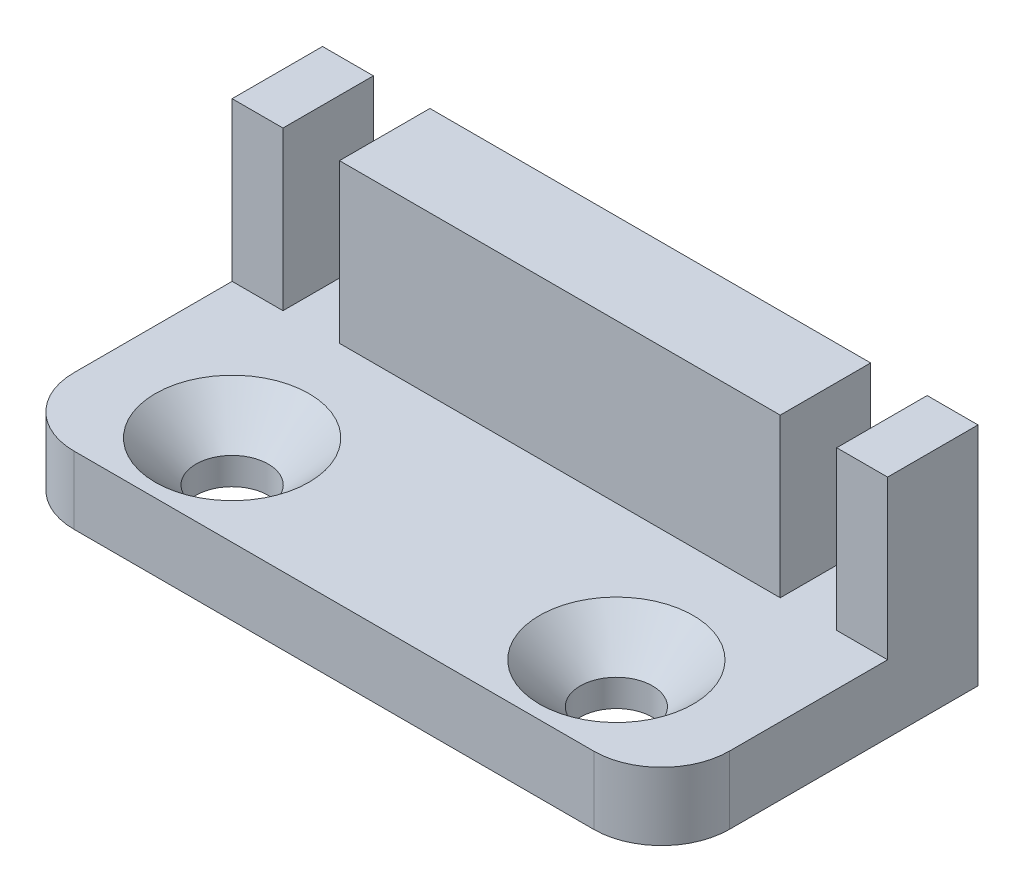
SolidWorks part; units mm, degrees
ref_plane "Front Plane" through (0, 0, 0) normal (0, 0, 1) x (1, 0, 0)
ref_plane "Top Plane" through (0, 0, 0) normal (0, 1, 0) x (1, 0, 0)
ref_plane "Right Plane" through (0, 0, 0) normal (1, 0, 0) x (0, 0, -1)
sketch "Sketch7" plane through (0, 0, 0) normal (0, 0, 1) x (1, 0, 0)
  line L1 (0, 0) -> (29, 0)
  line L2 (0, 0) -> (0, 10)
  line L3 (0, 10) -> (29, 10)
  line L4 (29, 0) -> (29, 10)
  dimension "D1" = 10
  dimension "D2" = 29
extrude "Boss-Extrude5" add sketch "Sketch7" along normal blind 4
sketch "Sketch8" plane through (0, 0, 4) normal (0, 0, 1) x (1, 0, 0)
  line L0 (29, 0) -> (29, 10) construction
  line L1 (0, 0) -> (29, 0)
  line L2 (0, 0) -> (0, 3)
  line L3 (0, 3) -> (29, 3)
  line L4 (29, 0) -> (29, 3)
  dimension "D1" = 3
extrude "Boss-Extrude6" add sketch "Sketch8" along normal blind 10
sketch "Sketch9" plane through (0, 10, 0) normal (0, 1, 0) x (1, 0, 0)
  line L0 (29, 0) -> (0, 0) construction
  line L1 (4.75, 0) -> (2.25, 0)
  line L2 (4.75, 0) -> (4.75, -4)
  line L3 (4.75, -4) -> (2.25, -4)
  line L4 (2.25, 0) -> (2.25, -4)
  line L5 (29, -4) -> (0, -4) construction
  line L6 (3.5, 0) -> (3.5, -4) construction
  line L11 (0, -4) -> (0, 0) construction
  line L12 (14.5, 0) -> (14.5, -14) construction
  line L13 (29, -14) -> (0, -14) construction
  line L16 (24.25, -4) -> (26.75, -4)
  line L17 (26.75, 0) -> (26.75, -4)
  line L18 (24.25, 0) -> (26.75, 0)
  line L23 (24.25, 0) -> (24.25, -4)
  dimension "D1" = 3.5
  dimension "D2" = 2.5
extrude "Cut-Extrude2" cut sketch "Sketch9" against normal up to surface (7 mm away) up to face at (14.5, 3, 9)
sketch "Sketch10" plane through (0, 3, 0) normal (0, 1, 0) x (1, 0, 0)
  line L0 (0, -10) -> (29, -10) construction
  line L1 (0, -14) -> (0, -4) construction
  line L2 (29, -14) -> (29, -4) construction
  line L3 (29, -14) -> (0, -14) construction
  circle A0 centre (6, -10) radius 1.6
  circle A1 centre (23, -10) radius 1.6
  dimension "D1" = 3.2
  dimension "D2" = 3.2
  dimension "D3" = 6
  dimension "D4" = 6
  dimension "D5" = 4
extrude "Cut-Extrude3" cut sketch "Sketch10" against normal up to next
chamfer "Chamfer1" distance 1.8 angle 45 2 edges at (23, 3, 11.6) (6, 3, 11.6)
fillet "Fillet1" radius 3 2 edges at (0, 1.5, 14) (29, 1.5, 14)
